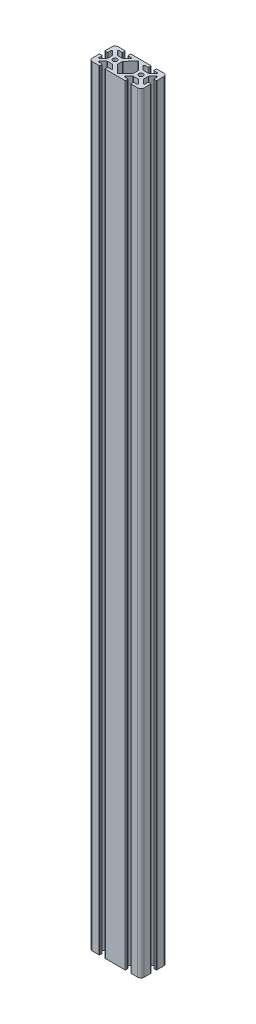
SolidWorks part; units mm, degrees
material "4032-T6"
ref_plane "Front Plane" through (0, 0, 0) normal (0, 0, 1) x (1, 0, 0)
ref_plane "Top Plane" through (0, 0, 0) normal (0, 1, 0) x (1, 0, 0)
ref_plane "Right Plane" through (0, 0, 0) normal (1, 0, 0) x (0, 0, -1)
sketch "Sketch1" plane through (0, 0, 0) normal (0, 1, 0) x (1, 0, 0)
  line L1 (5, 0) -> (75, 0)
  line L2 (0, -5) -> (0, -35)
  line L3 (5, -40) -> (75, -40)
  line L4 (80, -5) -> (80, -35)
  arc A0 (75, -40) -> (80, -35) centre (75, -35) ccw
  arc A1 (80, -5) -> (75, 0) centre (75, -5) ccw
  arc A2 (5, -40) -> (0, -35) centre (5, -35) cw
  arc A3 (0, -5) -> (5, 0) centre (5, -5) cw
  point P7 (80, -40)
  point P10 (80, 0)
  point P15 (0, 0)
  dimension "D3" = 5
  dimension "D1" = 80
  dimension "D2" = 40
extrude "Boss-Extrude1" add sketch "Sketch1" along normal blind 1190 contours L3 A0 L4 A1 L1 A3 L2 A2
sketch "Sketch3" plane through (0, 1190, 0) normal (0, 1, 0) x (1, 0, 0)
  line L0 (40, -2.5254) -> (40, -32.3671)
  line L1 (0, -5) -> (0, -35) construction
  line L2 (5, 0) -> (75, 0) construction
  circle A0 centre (20, -20) radius 3.4
  dimension "D4" = 6.8
  dimension "D1" = 40
  dimension "D2" = 20
  dimension "D3" = 20
extrude "Cut-Extrude1" cut sketch "Sketch3" against normal through all contours A0
ref_plane "mirro-plane" through (40, 0, 0) normal (1, 0, 0) x (0, 0, -1)
mirror "Mirror3" about plane through (40, 0, 0) normal (1, 0, 0) of "Cut-Extrude1"
ref_plane "sk5mirrorPlane" through (0, 0, 20) normal (0, 0, 1) x (1, 0, 0)
sketch "Sketch7" plane through (0, 0, 0) normal (0, -1, 0) x (-1, 0, 0)
  line L2 (-5, -40) -> (-75, -40) construction
  line L4 (-15.9, -40) -> (-24.1, -40)
  line L8 (-15.9, -40) -> (-15.9, -36.5)
  line L12 (-16.3092, -27.8) -> (-23.6908, -27.8)
  line L23 (-10.5103, -35.5) -> (-14.9, -35.5)
  line L25 (-24.1, -40) -> (-24.1, -36.5)
  line L27 (-15.6082, -28.0868) -> (-9.8093, -33.7868)
  line L31 (-29.4898, -35.5) -> (-25.1, -35.5)
  line L43 (-24.3918, -28.0868) -> (-30.1908, -33.7868)
  arc A0 (-24.3918, -28.0868) -> (-23.6908, -27.8) centre (-23.6908, -28.8) cw
  arc A1 (-16.3092, -27.8) -> (-15.6082, -28.0868) centre (-16.3092, -28.8) cw
  arc A2 (-30.1908, -33.7868) -> (-29.4898, -35.5) centre (-29.4898, -34.5) ccw
  arc A3 (-9.8093, -33.7868) -> (-10.5103, -35.5) centre (-10.5103, -34.5) cw
  arc A4 (-25.1, -35.5) -> (-24.1, -36.5) centre (-25.1, -36.5) cw
  arc A5 (-14.9, -35.5) -> (-15.9, -36.5) centre (-14.9, -36.5) ccw
  point P96 (-24.1, -35.5)
  dimension "D17" = 0
  dimension "D18" = 1
  dimension "D8" = 12.2
extrude "Cut-Extrude2" cut sketch "Sketch7" against normal through all
fillet "Fillet1" radius 1 2 edges at (15.9, 595, 40) (24.1, 595, 40)
mirror "Mirror8" about plane through (40, 0, 0) normal (1, 0, 0) of "Cut-Extrude2"
fillet "Fillet2" radius 1 1 edges at (55.9, 595, 40)
fillet "Fillet3" radius 1 1 edges at (64.1, 595, 40)
sketch "Sketch9" plane through (0, 0, 0) normal (0, 1, 0) x (1, 0, 0)
  line L1 (14.8998, -4.5007) -> (10.4505, -4.5007)
  line L3 (24.0998, -3.5) -> (24.1, 0)
  line L4 (15.8998, -3.5008) -> (15.9, 0)
  line L5 (15.9, 0) -> (24.1, 0)
  line L6 (16.1497, -12.2) -> (23.8503, -12.2)
  line L7 (5, 0) -> (75, 0) construction
  line L8 (25.0998, -4.5) -> (29.5503, -4.5)
  line L12 (9.7434, -6.2078) -> (15.4426, -11.9071)
  line L16 (24.5574, -11.9071) -> (30.2574, -6.2071)
  arc A0 (15.8998, -3.5008) -> (14.8998, -4.5007) centre (14.8998, -3.5007) cw
  arc A1 (24.0998, -3.5) -> (25.0998, -4.5) centre (25.0998, -3.5) ccw
  arc A2 (29.5503, -4.5) -> (30.2574, -6.2071) centre (29.5503, -5.5) cw
  arc A3 (24.5574, -11.9071) -> (23.8503, -12.2) centre (23.8503, -11.2) cw
  arc A4 (9.7434, -6.2078) -> (10.4505, -4.5007) centre (10.4505, -5.5007) cw
  arc A5 (15.4426, -11.9071) -> (16.1497, -12.2) centre (16.1497, -11.2) ccw
  dimension "D2" = 1
  dimension "D1" = 0
  dimension "D5" = 12.2
  dimension "D6" = 4.5
extrude "Cut-Extrude3" cut sketch "Sketch9" along normal through all
mirror "Mirror9" about plane through (40, 0, 0) normal (1, 0, 0) of "Cut-Extrude3"
sketch "Sketch10" plane through (0, 0, 0) normal (0, 1, 0) x (1, 0, 0)
  line L0 (4.5, -14.9) -> (4.5, -10.5861)
  line L4 (0, -24.1) -> (3.5, -24.1)
  line L5 (0, -15.9) -> (3.5, -15.9)
  line L8 (12.2, -23.4919) -> (12.2, -16.5081)
  line L10 (0, -5) -> (0, -35) construction
  line L13 (4.5, -29.4139) -> (4.5, -25.1)
  line L25 (11.9205, -24.1853) -> (6.2205, -30.1074)
  line L26 (11.9205, -15.8147) -> (6.2205, -9.8926)
  line L29 (0, -24.1) -> (0, -15.9)
  arc A0 (4.5, -14.9) -> (3.5, -15.9) centre (3.5, -14.9) cw
  arc A1 (3.5, -24.1) -> (4.5, -25.1) centre (3.5, -25.1) cw
  arc A2 (6.2205, -9.8926) -> (4.5, -10.5861) centre (5.5, -10.5861) ccw
  arc A3 (11.9205, -15.8147) -> (12.2, -16.5081) centre (11.2, -16.5081) cw
  arc A4 (11.9205, -24.1853) -> (12.2, -23.4919) centre (11.2, -23.4919) ccw
  arc A5 (4.5, -29.4139) -> (6.2205, -30.1074) centre (5.5, -29.4139) ccw
  dimension "D3" = 1
  dimension "D7" = 12.2
  dimension "D9" = 4.5
  dimension "D17" = 0
extrude "Cut-Extrude4" cut sketch "Sketch10" along normal through all
fillet "Fillet4" radius 1 1 edges at (24.1, 595, 0)
fillet "Fillet5" radius 1 1 edges at (64.1, 595, 0)
fillet "Fillet6" radius 1 1 edges at (55.9, 595, 0)
fillet "Fillet7" radius 1 1 edges at (15.9, 595, 0)
fillet "Fillet8" radius 1 1 edges at (0, 595, 24.1)
fillet "Fillet9" radius 1 1 edges at (0, 595, 15.9)
sketch "Sketch11" plane through (0, 0, 0) normal (0, 1, 0) x (1, 0, 0)
  line L0 (75.5, -29.6797) -> (75.5, -25.1)
  line L1 (80, -5) -> (80, -35) construction
  line L2 (67.5, -16.0953) -> (67.5, -23.9047)
  line L5 (75.5, -14.9) -> (75.5, -10.3203)
  line L7 (80, -24.1) -> (80, -15.9)
  line L8 (80, -5) -> (80, -35) construction
  line L13 (113.5168, -27.8) -> (113.5178, -27.6385)
  line L17 (67.8065, -15.3748) -> (73.8065, -9.5998)
  line L63 (67.8065, -24.6252) -> (73.8065, -30.4002)
  line L66 (76.5, -15.9) -> (80, -15.9)
  line L68 (76.5, -24.1) -> (80, -24.1)
  arc A44 (75.5, -25.1) -> (76.5, -24.1) centre (76.5, -25.1) cw
  arc A45 (75.5, -14.9) -> (76.5, -15.9) centre (76.5, -14.9) ccw
  arc A46 (73.8065, -9.5998) -> (75.5, -10.3203) centre (74.5, -10.3203) cw
  arc A47 (73.8065, -30.4002) -> (75.5, -29.6797) centre (74.5, -29.6797) ccw
  arc A48 (67.8065, -24.6252) -> (67.5, -23.9047) centre (68.5, -23.9047) cw
  arc A49 (67.8065, -15.3748) -> (67.5, -16.0953) centre (68.5, -16.0953) ccw
  dimension "D3" = 1
  dimension "D2" = 4.5
  dimension "D4" = 12.5
ref_plane "offset1" through (60, 0, 0) normal (1, 0, 0) x (0, 0, -1)
mirror "Mirror10" about plane through (40, 0, 0) normal (1, 0, 0) of "Cut-Extrude4"
fillet "Fillet10" radius 1 1 edges at (80, 595, 15.9)
fillet "Fillet11" radius 1 1 edges at (80, 595, 24.1)
mirror "Mirror11" about plane through (60, 0, 0) normal (1, 0, 0) of "Mirror10"
ref_plane "Plane2" through (20, 0, 0) normal (-1, 0, 0) x (0, 0, 1)
mirror "Mirror12" about plane through (20, 0, 0) normal (-1, 0, 0) of "Cut-Extrude4"
sketch "Sketch12" plane through (0, 0, 0) normal (0, -1, 0) x (-1, 0, 0)
  line L0 (-28.0795, -24.1853) -> (-39.3271, -35.8711)
  line L2 (-51.9226, -24.2109) -> (-40.7702, -35.8689)
  line L4 (-39.2795, -4.1783) -> (-28.0795, -15.8147)
  line L7 (-51.9205, -15.8147) -> (-40.7205, -4.1783)
  line L8 (-27.8, -23.4919) -> (-27.8, -16.5081)
  line L9 (-52.2, -23.5196) -> (-52.2, -16.5081)
  line L10 (-52.2, -23.4919) -> (-52.2, -16.5081) construction
  line L11 (-27.8, -23.4919) -> (-27.8, -16.5081) construction
  arc A0 (-39.2795, -4.1783) -> (-40.7205, -4.1783) centre (-40, -4.8718) ccw
  arc A1 (-39.3271, -35.8711) -> (-40.7702, -35.8689) centre (-40.0476, -35.1776) cw
  arc A2 (-51.9205, -15.8147) -> (-52.2, -16.5081) centre (-51.2, -16.5081) ccw
  arc A3 (-52.2, -23.5196) -> (-51.9226, -24.2109) centre (-51.2, -23.5196) ccw
  arc A4 (-28.0795, -15.8147) -> (-27.8, -16.5081) centre (-28.8, -16.5081) cw
  arc A5 (-27.8, -23.4919) -> (-28.0795, -24.1853) centre (-28.8, -23.4919) cw
  dimension "D3" = 1
  dimension "D4" = 1
  dimension "D1" = 0
  dimension "D2" = 0
extrude "Cut-Extrude5" cut sketch "Sketch12" against normal through all
